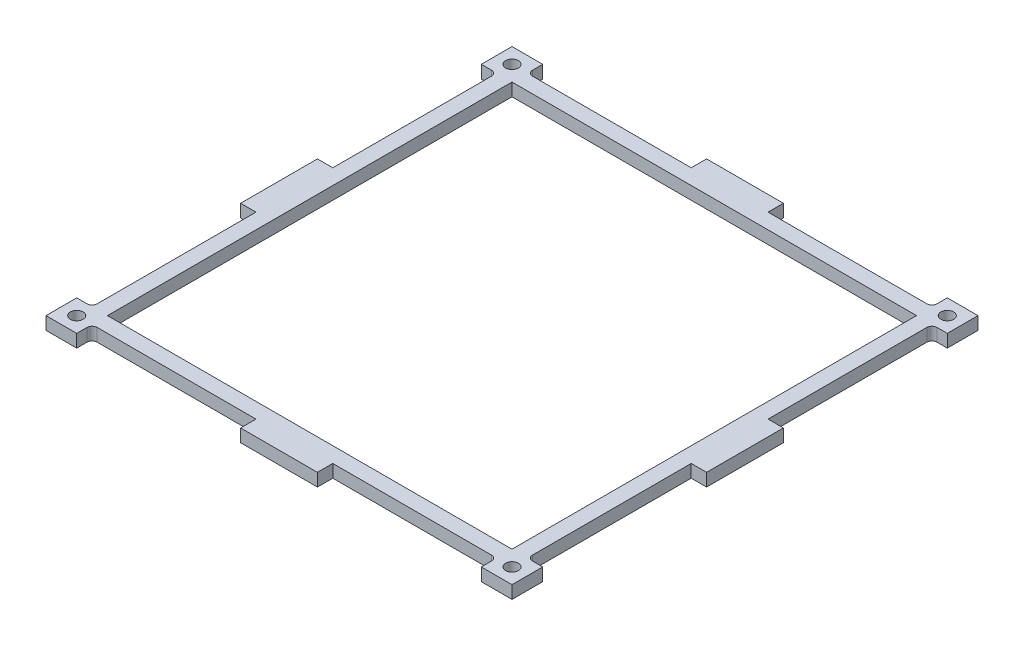
SolidWorks part; units mm, degrees
ref_plane "Alzado" through (0, 0, 0) normal (0, 0, 1) x (1, 0, 0)
ref_plane "Planta" through (0, 0, 0) normal (0, 1, 0) x (1, 0, 0)
ref_plane "Vista lateral" through (0, 0, 0) normal (1, 0, 0) x (0, 0, -1)
sketch "Croquis1" plane through (0, 0, 0) normal (0, 1, 0) x (1, 0, 0)
  line L0 (-79, 79) -> (-91, 91) construction
  line L1 (0, 0) -> (-79, 0) construction
  line L2 (0, 0) -> (0, 79) construction
  line L3 (0, 79) -> (-79, 79)
  line L4 (-79, 0) -> (-79, 79)
  line L5 (0, 0) -> (-85, 0) construction
  line L6 (0, 0) -> (0, 85) construction
  line L7 (-15, 85) -> (-79, 85)
  line L8 (-85, 15) -> (-85, 79)
  line L13 (-85, 79) -> (-91, 79)
  line L14 (-79, 85) -> (-79, 91)
  line L15 (-79, 91) -> (-91, 91)
  line L16 (-91, 79) -> (-91, 91)
  line L17 (-85, 79) -> (-79, 79) construction
  line L18 (-79, 79) -> (-79, 85) construction
  line L19 (-79, 91) -> (-15, 91) construction
  line L22 (0, 91) -> (-15, 91)
  line L23 (-15, 85) -> (-15, 91)
  line L24 (0, 91) -> (0, 79) construction
  line L25 (-15, 85) -> (0, 85) construction
  line L26 (-91, 15) -> (-91, 79) construction
  line L29 (-85, 15) -> (-91, 15)
  line L30 (-91, 0) -> (-91, 15)
  line L31 (-91, 0) -> (-85, 0) construction
  line L32 (-85, 0) -> (-85, 15) construction
  line L33 (-91, 0) -> (-79, 0)
  line L34 (0, 79) -> (0, 91)
  line L35 (79, 0) -> (79, 79)
  line L36 (79, 0) -> (91, 0)
  line L37 (91, 0) -> (91, 15)
  line L38 (85, 15) -> (91, 15)
  line L39 (85, 15) -> (85, 79)
  line L40 (85, 79) -> (91, 79)
  line L41 (91, 79) -> (91, 91)
  line L42 (79, 91) -> (91, 91)
  line L43 (79, 85) -> (79, 91)
  line L44 (15, 85) -> (79, 85)
  line L45 (15, 85) -> (15, 91)
  line L46 (0, 91) -> (15, 91)
  line L47 (0, 91) -> (0, 79)
  line L48 (0, 79) -> (79, 79)
  line L49 (0, -79) -> (79, -79)
  line L50 (0, -79) -> (0, -91)
  line L51 (0, -91) -> (15, -91)
  line L52 (15, -85) -> (15, -91)
  line L53 (15, -85) -> (79, -85)
  line L54 (79, -85) -> (79, -91)
  line L55 (79, -91) -> (91, -91)
  line L56 (91, -79) -> (91, -91)
  line L57 (85, -79) -> (91, -79)
  line L58 (85, -15) -> (85, -79)
  line L59 (85, -15) -> (91, -15)
  line L60 (91, 0) -> (91, -15)
  line L61 (91, 0) -> (79, 0)
  line L62 (79, 0) -> (79, -79)
  line L63 (-79, 0) -> (-79, -79)
  line L64 (-79, 0) -> (-91, 0)
  line L65 (-91, 0) -> (-91, -15)
  line L66 (-85, -15) -> (-91, -15)
  line L67 (-85, -15) -> (-85, -79)
  line L68 (-85, -79) -> (-91, -79)
  line L69 (-91, -79) -> (-91, -91)
  line L70 (-79, -91) -> (-91, -91)
  line L71 (-79, -85) -> (-79, -91)
  line L72 (-15, -85) -> (-79, -85)
  line L73 (-15, -85) -> (-15, -91)
  line L74 (0, -91) -> (-15, -91)
  line L75 (0, -91) -> (0, -79)
  line L76 (0, -79) -> (-79, -79)
  circle A0 centre (-85, 85) radius 2.5
  circle A1 centre (85, 85) radius 2.5
  circle A2 centre (85, -85) radius 2.5
  circle A3 centre (-85, -85) radius 2.5
  dimension "D3" = 5
  dimension "D1" = 79
  dimension "D2" = 6
  dimension "D4" = 85
  dimension "D5" = 15
  dimension "D6" = 4
extrude "Saliente-Extruir1" add sketch "Croquis1" along normal blind 5 contours L34 L48 L35 L36 L37 L38 L39 L40 L41 L42 L43 L44 L45 L46 A1 | L36 L62 L49 L50 L51 L52 L53 L54 L55 L56 L57 L58 L59 L60 A2 | L50 L76 L63 L33 L65 L66 L67 L68 L69 L70 L71 L72 L73 L74 A3 | L3 L34 L22 L23 L7 L14 L15 L16 L13 L8 L29 L30 L33 L4 A0
fillet "Redondeo1" radius 2 8 edges at (-85, 2.5, 79) (-79, 2.5, 85) (-85, 2.5, -79) (-79, 2.5, -85) (79, 2.5, -85) (85, 2.5, -79) (85, 2.5, 79) (79, 2.5, 85)
